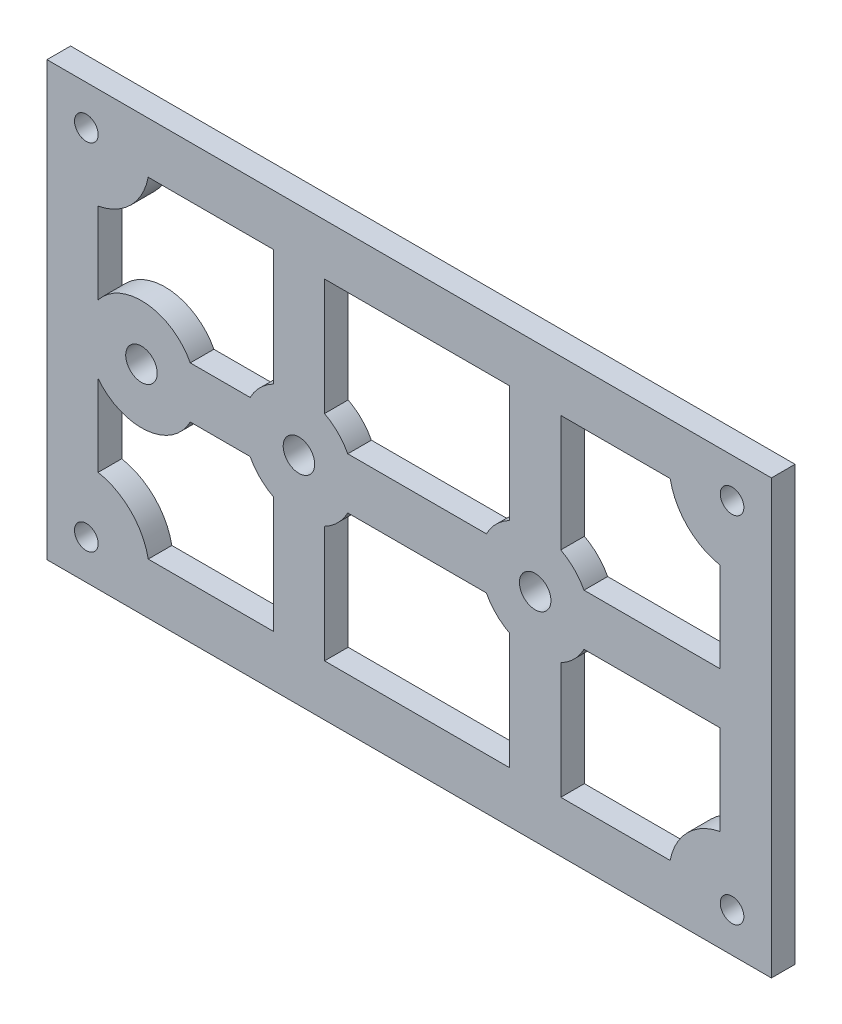
SolidWorks part; units mm, degrees
ref_plane "Front Plane" through (0, 0, 0) normal (0, 0, 1) x (1, 0, 0)
ref_plane "Top Plane" through (0, 0, 0) normal (0, 1, 0) x (1, 0, 0)
ref_plane "Right Plane" through (0, 0, 0) normal (1, 0, 0) x (0, 0, -1)
sketch "Sketch1" plane through (0, 0, 0) normal (0, 0, 1) x (1, 0, 0)
  line L0 (12.75, -21) -> (12.75, -6.1998)
  line L1 (-46, 27.5) -> (46, 27.5)
  line L2 (-46, 27.5) -> (-46, -27.5)
  line L3 (-46, -27.5) -> (46, -27.5)
  line L4 (46, 27.5) -> (46, -27.5)
  line L5 (-39.5, 4.3301) -> (-39.5, 14.6419)
  line L6 (-27.8002, -3.25) -> (-20.1998, -3.25)
  line L7 (19.25, -21) -> (19.25, -6.1998)
  line L9 (-33.1419, -21) -> (-17.25, -21)
  line L10 (0, 0) -> (-16, 0) construction
  line L11 (-33.1419, 21) -> (-17.25, 21)
  line L12 (39.5, 3.25) -> (39.5, 14.6419)
  line L13 (-10.75, -21) -> (-10.75, -6.1998)
  line L14 (-17.25, -21) -> (-17.25, -6.1998)
  line L15 (-10.75, 21) -> (12.75, 21)
  line L16 (39.5, 3.25) -> (22.1998, 3.25)
  line L17 (-20.1998, 3.25) -> (-27.8002, 3.25)
  line L18 (-14, 0) -> (-14, -27.5) construction
  line L19 (-39.5, -14.6419) -> (-39.5, -4.3301)
  line L20 (16, 0) -> (16, -27.5) construction
  line L21 (-7.8002, -3.25) -> (9.8002, -3.25)
  line L22 (-17.25, 6.1998) -> (-17.25, 21)
  line L23 (-10.75, 6.1998) -> (-10.75, 21)
  line L25 (-39.5, 22.5) -> (-39.5, 23.5563)
  line L26 (0, 21) -> (0, -21) construction
  line L28 (9.8002, 3.25) -> (-7.8002, 3.25)
  line L29 (12.75, 6.1998) -> (12.75, 21)
  line L31 (19.25, 6.1998) -> (19.25, 21)
  line L32 (22.1998, -3.25) -> (39.5, -3.25)
  line L34 (19.25, 21) -> (33.1419, 21)
  line L35 (19.25, -21) -> (33.1419, -21)
  line L36 (-10.75, -21) -> (12.75, -21)
  line L39 (39.5, -14.6419) -> (39.5, -3.25)
  circle A0 centre (-34, 0) radius 2
  circle A1 centre (-14, 0) radius 2
  circle A2 centre (16, 0) radius 2
  circle A4 centre (-41, 22.5) radius 1.5
  arc A5 (-39.5, 14.6419) -> (-33.1419, 21) centre (-41, 22.5) ccw
  circle A6 centre (41, 22.5) radius 1.5
  arc A8 (33.1419, 21) -> (39.5, 14.6419) centre (41, 22.5) ccw
  arc A9 (-39.5, -4.3301) -> (-27.8002, -3.25) centre (-34, 0) ccw
  circle A10 centre (41, -22.5) radius 1.5
  arc A11 (33.1419, -21) -> (39.5, -14.6419) centre (41, -22.5) cw
  circle A13 centre (-41, -22.5) radius 1.5
  arc A15 (9.8002, -3.25) -> (12.75, -6.1998) centre (16, 0) ccw
  arc A16 (-7.8002, 3.25) -> (-10.75, 6.1998) centre (-14, 0) ccw
  arc A17 (-39.5, -14.6419) -> (-33.1419, -21) centre (-41, -22.5) cw
  arc A18 (-17.25, 6.1998) -> (-20.1998, 3.25) centre (-14, 0) ccw
  arc A19 (-20.1998, -3.25) -> (-17.25, -6.1998) centre (-14, 0) ccw
  arc A20 (-27.8002, 3.25) -> (-39.5, 4.3301) centre (-34, 0) ccw
  arc A21 (12.75, 6.1998) -> (9.8002, 3.25) centre (16, 0) ccw
  arc A22 (19.25, -6.1998) -> (22.1998, -3.25) centre (16, 0) ccw
  arc A23 (22.1998, 3.25) -> (19.25, 6.1998) centre (16, 0) ccw
  arc A24 (-10.75, -6.1998) -> (-7.8002, -3.25) centre (-14, 0) ccw
  point P0 (0, 0)
  point P13 (0, -27.5)
  point P15 (-0.0179, -21)
  point P20 (0, 0)
  point P25 (0, 0)
  point P27 (-14, -27.5)
  point P33 (16, -27.5)
  point P34 (0, 0)
  point P41 (-0.154, 0.1567)
  point P44 (0.0229, 0)
  point P49 (1.3858, 0)
  point P51 (0, 0)
  point P59 (0, 0)
  point P61 (-0.0233, 0)
  point P69 (20.3844, 0)
  point P78 (46, 0)
  point P80 (18, 0)
  point P82 (9.0104, 0)
  point P83 (0, 0)
  point P84 (0, 27.5)
  point P85 (0, 21)
  point P86 (-46, 0)
  point P87 (-36, 0)
  point P88 (-16, 0)
  dimension "D4" = 4
  dimension "D5" = 27.5
  dimension "D6" = 4
  dimension "D9" = 4
  dimension "D20" = 3
  dimension "D21" = 5
  dimension "D22" = 6.5
  dimension "D23" = 3
  dimension "D24" = 5
  dimension "D25" = 5
  dimension "D26" = 6.5
  dimension "D27" = 5
  dimension "D30" = 5
  dimension "D31" = 5
  dimension "D19" = 6.5
  dimension "D32" = 6.5
  dimension "D35" = 3
  dimension "D36" = 5
  dimension "D38" = 3
  dimension "D1" = 55
  dimension "D7" = 20
  dimension "D8" = 27.5
  dimension "D10" = 30
  dimension "D12" = 5
  dimension "D13" = 6.5
  dimension "D14" = 6.5
  dimension "D15" = 12
  dimension "D16" = 6.5
  dimension "D17" = 6.5
  dimension "D18" = 6.5
  dimension "D28" = 5
  dimension "D29" = 3.25
  dimension "D33" = 30
  dimension "D34" = 5
  dimension "D37" = 6.5
  dimension "D39" = 5
extrude "Boss-Extrude1" add sketch "Sketch1" along normal blind 3
